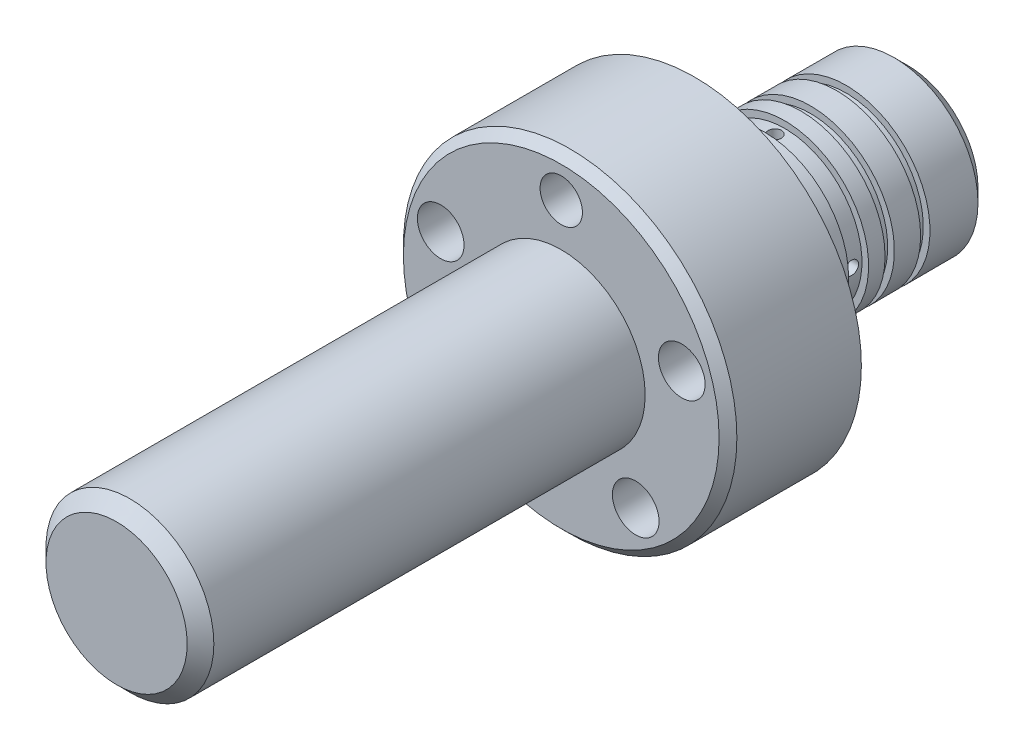
SolidWorks part; units mm, degrees
ref_plane "Front Plane" through (0, 0, 0) normal (0, 0, 1) x (1, 0, 0)
ref_plane "Top Plane" through (0, 0, 0) normal (0, 1, 0) x (1, 0, 0)
ref_plane "Right Plane" through (0, 0, 0) normal (1, 0, 0) x (0, 0, -1)
sketch "Sketch1" plane through (0, 0, 0) normal (0, 0, 1) x (1, 0, 0)
  circle A1 centre (0, 0) radius 18.875
  dimension "D2" = 37.75
extrude "Boss-Extrude1" add sketch "Sketch1" along normal blind 47.85
sketch "Sketch2" plane through (0, 0, 47.85) normal (0, 0, 1) x (1, 0, 0)
  circle A0 centre (0, 0) radius 37.5
  dimension "D1" = 75
extrude "Boss-Extrude2" add sketch "Sketch2" along normal blind 30
sketch "Sketch11" plane through (0, 0, 77.85) normal (0, 0, 1) x (1, 0, 0)
  line L0 (0, 0) -> (0, 37.5) construction
  circle A0 centre (0, 0) radius 37.5 construction
  circle A1 centre (0, 0) radius 28.5 construction
  circle A2 centre (0, 28.5) radius 3.125
  point P19 (0, 0)
  dimension "D1" = 57
  dimension "D2" = 6.25
extrude "Cut-Extrude4" cut sketch "Sketch11" against normal up to surface (30 mm away) up to face at (18.875, 0, 47.85)
sketch "Sketch12" plane through (0, 0, 77.85) normal (0, 0, 1) x (1, 0, 0)
  circle A0 centre (0, 28.5) radius 4.7625
  point P16 (0, 0)
  dimension "D1" = 9.525
extrude "Cut-Extrude5" cut sketch "Sketch12" against normal blind 8
sketch "Sketch13" plane through (0, 0, 0) normal (1, 0, 0) x (0, 0, -1)
  line L0 (0, 0) -> (-47.85, 0) construction
  line L1 (0, -18.875) -> (0, 18.875) construction
  line L2 (-47.85, -37.5) -> (-47.85, 37.5) construction
  line L3 (-14.85, 0) -> (-14.85, 18.875) construction
  line L4 (0, 18.875) -> (-47.85, 18.875) construction
  line L5 (-22.85, 0) -> (-22.85, 18.875) construction
  line L6 (-35.85, 0) -> (-35.85, 18.875) construction
  line L7 (-39.85, 0) -> (-39.85, 18.875) construction
  line L8 (-47.85, -18.875) -> (-47.85, 18.875) construction
  line L10 (-29.85, 18.475) -> (-29.85, 0) construction
  line L11 (-47.85, -18.875) -> (0, -18.875) construction
  line L12 (-15.9, 17.375) -> (-47.85, 17.375) construction
  line L13 (-15.9, 20.375) -> (-13.8, 20.375)
  line L14 (-15.9, 20.375) -> (-15.9, 17.375)
  line L15 (-15.9, 17.375) -> (-13.8, 17.375)
  line L16 (-13.8, 20.375) -> (-13.8, 17.375)
  line L17 (-15.9, 20.375) -> (-13.8, 17.375) construction
  line L18 (-15.9, 17.375) -> (-13.8, 20.375) construction
  line L19 (0, 0) -> (0, 17.875) construction
  line L20 (-23.9, 20.375) -> (-21.8, 20.375)
  line L21 (-23.9, 20.375) -> (-23.9, 17.375)
  line L22 (-23.9, 17.375) -> (-21.8, 17.375)
  line L23 (-21.8, 20.375) -> (-21.8, 17.375)
  line L24 (-23.9, 20.375) -> (-21.8, 17.375) construction
  line L25 (-23.9, 17.375) -> (-21.8, 20.375) construction
  line L26 (-36.9, 20.375) -> (-34.8, 20.375)
  line L27 (-36.9, 20.375) -> (-36.9, 17.375)
  line L28 (-36.9, 17.375) -> (-34.8, 17.375)
  line L29 (-34.8, 20.375) -> (-34.8, 17.375)
  line L30 (-36.9, 20.375) -> (-34.8, 17.375) construction
  line L31 (-36.9, 17.375) -> (-34.8, 20.375) construction
  line L32 (-40.9, 20.375) -> (-38.8, 20.375)
  line L33 (-40.9, 20.375) -> (-40.9, 17.375)
  line L34 (-40.9, 17.375) -> (-38.8, 17.375)
  line L35 (-38.8, 20.375) -> (-38.8, 17.375)
  line L36 (-40.9, 20.375) -> (-38.8, 17.375) construction
  line L37 (-40.9, 17.375) -> (-38.8, 20.375) construction
  line L38 (-16.9262, 17.375) -> (-16.9262, 19.375) construction
  line L40 (-32.1, 19.575) -> (-27.6, 19.575)
  line L41 (-32.1, 19.575) -> (-32.1, 17.375)
  line L42 (-32.1, 17.375) -> (-27.6, 17.375)
  line L43 (-27.6, 19.575) -> (-27.6, 17.375)
  line L44 (-32.1, 19.575) -> (-27.6, 17.375) construction
  line L45 (-32.1, 17.375) -> (-27.6, 19.575) construction
  point P21 (-29.85, 9.2375)
  dimension "D1" = 8
  dimension "D2" = 12
  dimension "D3" = 25
  dimension "D4" = 33
  dimension "D5" = 1.5
  dimension "D6" = 2.1
  dimension "D7" = 2.1
  dimension "D8" = 2.1
  dimension "D9" = 2.1
  dimension "D10" = 2
  dimension "D11" = 4.5
  dimension "D12" = 18
revolve "Cut-Revolve1" cut sketch "Sketch13" angle 360 about L0
sketch "Sketch18" plane through (0, 0, 77.85) normal (0, 0, 1) x (1, 0, 0)
  circle A0 centre (0, 28.5) radius 3.125 construction
  circle A1 centre (27.1051, 8.807) radius 3.125
  circle A2 centre (16.7519, -23.057) radius 3.125
  circle A3 centre (-16.7519, -23.057) radius 3.125
  circle A4 centre (-27.1051, 8.807) radius 3.125
  point P13 (0, 0)
  dimension "D1" = 6.25
  dimension "D2" = 5
extrude "Cut-Extrude8" cut sketch "Sketch18" against normal up to surface (30 mm away) up to face at (3.125, 28.5, 47.85)
sketch "Sketch19" plane through (0, 0, 77.85) normal (0, 0, 1) x (1, 0, 0)
  circle A0 centre (0, 28.5) radius 5.25 construction
  circle A1 centre (27.1051, 8.807) radius 5.25
  circle A2 centre (16.7519, -23.057) radius 5.25
  circle A3 centre (-16.7519, -23.057) radius 5.25
  circle A4 centre (-27.1051, 8.807) radius 5.25
  point P13 (0, 0)
  dimension "D1" = 10.5
  dimension "D2" = 5
extrude "Cut-Extrude9" cut sketch "Sketch19" against normal blind 27
ref_plane "Plane4" through (0, 38, 0) normal (0, 1, 0) x (1, 0, 0)
chamfer "Chamfer1" distance 2 angle 45 1 edges at (37.5, 0, 77.85)
sketch "Sketch20" plane through (0, 0, 77.85) normal (0, 0, 1) x (1, 0, 0)
  circle A0 centre (0, 0) radius 18.875
  dimension "D1" = 37.75
extrude "Boss-Extrude3" add sketch "Sketch20" along normal blind 100
hole_wizard "Ø8.0mm Dowel Hole1" positions "Sketch22" profile "Sketch24" hole size "Ø8.0" standard "ANSI Metric"
sketch "Sketch22" plane through (0, 0, 0) normal (0, 0, -1) x (-1, 0, 0)
  point P0 (0, 0)
sketch "Sketch24" plane through (0, 0, 0) normal (1, 0, 0) x (0, 1, 0)
  line L0 (0, 0) -> (0, 80.2534)
  line L1 (0, 80.2534) -> (4, 77.85)
  line L2 (4, 77.85) -> (4, 0)
  line L5 (4, 0) -> (0, 0)
  line L10 (0, 80.2534) -> (-4, 77.85) construction
  line L11 (0, -6.35) -> (0, 107.95) construction
  dimension "Hole Dia." = 8
  dimension "Hole Depth" = 77.85
  dimension "Drill Angle" = 118
sketch "Sketch25" plane through (0, 0, 0) normal (1, 0, 0) x (0, 0, -1)
  line L0 (-61.85, 37.5) -> (-61.85, -37.5) construction
  line L2 (-75.85, -37.5) -> (-47.85, -37.5) construction
  line L4 (-65.25, 0) -> (-65.25, -12.5)
  line L5 (-65.85, -22.5) -> (-71.85, -22.5)
  line L6 (-71.85, -22.5) -> (-71.85, -41.1155)
  line L7 (-71.85, -41.1155) -> (-61.85, -41.1155)
  line L8 (-61.85, -41.1155) -> (-61.85, 0)
  line L9 (-65.25, 0) -> (-61.85, 0)
  line L10 (-65.85, -22.5) -> (-65.85, -12.5)
  line L11 (-65.85, -12.5) -> (-65.25, -12.5)
  line L12 (-47.85, 37.5) -> (-75.85, 37.5) construction
  point P10 (-61.85, 0)
  dimension "D1" = 3.4
  dimension "D2" = 10
  dimension "D3" = 10
  dimension "D4" = 4
  dimension "D5" = 15
revolve "Cut-Revolve2" cut sketch "Sketch25" angle 360 about L0
chamfer "Chamfer2" distance 3 angle 45 2 edges at (18.875, 0, 0) (18.875, 0, 177.85)
sketch "Sketch26" plane through (0, 0, 0) normal (0, 1, 0) x (1, 0, 0)
  line L0 (0, -27.6) -> (0, -32.1) construction
  line L1 (-17.375, -27.6) -> (17.375, -27.6) construction
  line L2 (18.875, -32.1) -> (-18.875, -32.1) construction
  circle A0 centre (0, -29.85) radius 1.5
  dimension "D1" = 3
extrude "Cut-Extrude10" cut sketch "Sketch26" against normal through all
pattern_circular "CirPattern1" count 4 over 360 about axis through (0, 0, 27.6) along (0, 0, -1) of "Cut-Extrude10"
